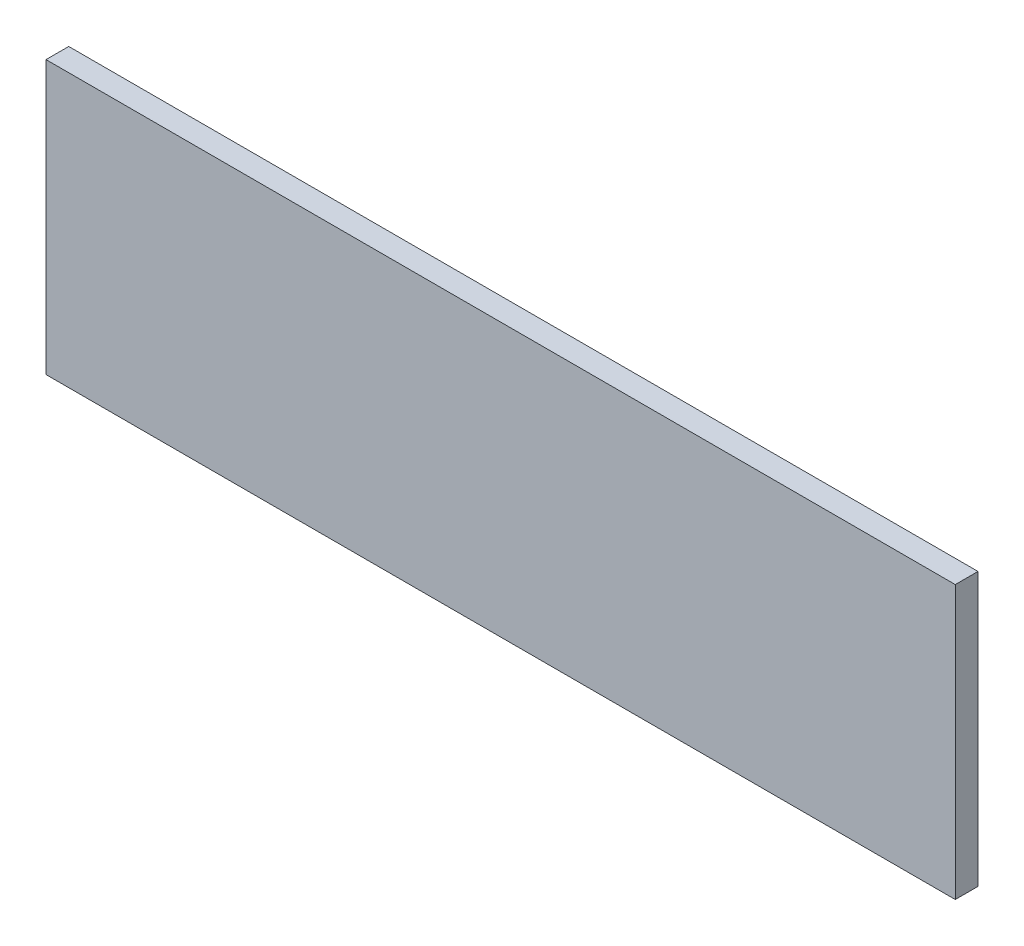
SolidWorks part; units mm, degrees
ref_plane "Front Plane" through (0, 0, 0) normal (0, 0, 1) x (1, 0, 0)
ref_plane "Top Plane" through (0, 0, 0) normal (0, 1, 0) x (1, 0, 0)
ref_plane "Right Plane" through (0, 0, 0) normal (1, 0, 0) x (0, 0, -1)
sketch "Sketch1" plane through (0, 0, 0) normal (0, 0, 1) x (1, 0, 0)
  line L1 (0, 0) -> (254, 0)
  line L2 (0, 0) -> (0, 76.2)
  line L3 (0, 76.2) -> (254, 76.2)
  line L4 (254, 0) -> (254, 76.2)
  dimension "D1" = 76.2
  dimension "D2" = 254
extrude "Boss-Extrude1" add sketch "Sketch1" along normal blind 6.35
